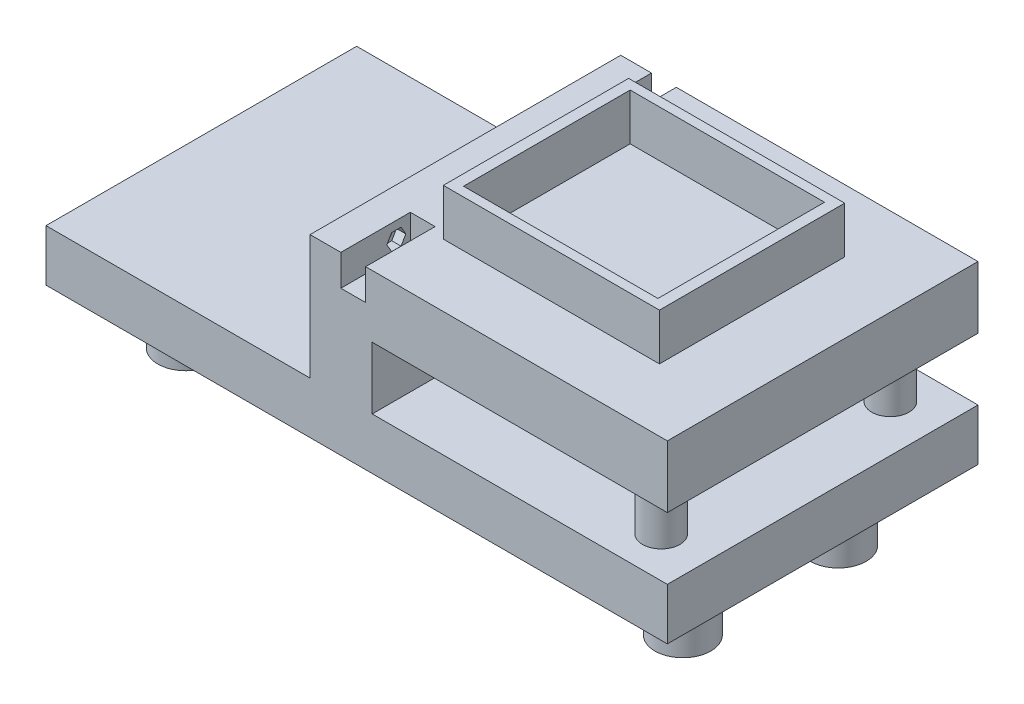
SolidWorks part; units mm, degrees
ref_plane "Front Plane" through (0, 0, 0) normal (0, 0, 1) x (1, 0, 0)
ref_plane "Top Plane" through (0, 0, 0) normal (0, 1, 0) x (1, 0, 0)
ref_plane "Right Plane" through (0, 0, 0) normal (1, 0, 0) x (0, 0, -1)
sketch "Sketch1" plane through (0, 0, 0) normal (0, 1, 0) x (1, 0, 0)
  line L7 (57.5, -50) -> (-57.5, -50)
  line L8 (57.5, -50) -> (57.5, 50)
  line L9 (57.5, 50) -> (-57.5, 50)
  line L10 (-57.5, -50) -> (-57.5, 50)
  line L11 (57.5, -50) -> (-57.5, 50) construction
  line L12 (57.5, 50) -> (-57.5, -50) construction
  point P0 (0, 0)
  dimension "D1" = 115
  dimension "D2" = 100
extrude "Boss-Extrude1" add sketch "Sketch1" along normal blind 20
sketch "Sketch8" plane through (0, 0, 0) normal (0, -1, 0) x (1, 0, 0)
  line L0 (57.5, -50) -> (-57.5, 50) construction
  line L1 (57.5, 50) -> (-57.5, -50) construction
  line L2 (57.5, 0) -> (-57.5, 0) construction
  line L3 (57.5, 50) -> (57.5, -50) construction
  line L4 (-57.5, -50) -> (-57.5, 50) construction
  line L5 (0, -50) -> (0, 50) construction
  line L6 (57.5, -50) -> (-57.5, -50) construction
  line L7 (-57.5, 50) -> (57.5, 50) construction
  circle A0 centre (0, 0) radius 7
  circle A1 centre (42.4079, -36.8764) radius 6
  circle A2 centre (42.4079, 36.8764) radius 6
  dimension "D1" = 12
  dimension "D3" = 14
  dimension "D2" = 20
extrude "Boss-Extrude4" add sketch "Sketch8" along normal blind 20
sketch "Sketch9" plane through (0, -20, 0) normal (0, -1, 0) x (1, 0, 0)
  line L0 (-57.5, 50) -> (57.5, 50) construction
  line L1 (57.5, -50) -> (-142.5, -50)
  line L2 (57.5, -50) -> (57.5, 50)
  line L3 (57.5, 50) -> (-142.5, 50)
  line L4 (-142.5, -50) -> (-142.5, 50)
  line L5 (57.5, -50) -> (-142.5, 50) construction
  line L6 (57.5, 50) -> (-142.5, -50) construction
  line L7 (57.5, 50) -> (57.5, -50) construction
  line L8 (57.5, -50) -> (-57.5, -50) construction
  point P4 (-42.5, 0)
  dimension "D1" = 200
extrude "Boss-Extrude5" add sketch "Sketch9" along normal blind 16.6
sketch "Sketch10" plane through (0, -36.6, 0) normal (0, -1, 0) x (1, 0, 0)
  line L0 (-42.5, -50) -> (-42.5, 50) construction
  line L1 (-142.5, -50) -> (57.5, -50) construction
  line L2 (57.5, 50) -> (-142.5, 50) construction
  line L3 (57.5, 0) -> (-142.5, 0) construction
  line L4 (57.5, -50) -> (57.5, 50) construction
  line L5 (-142.5, 50) -> (-142.5, -50) construction
  circle A0 centre (37.5, -25) radius 9
  circle A1 centre (-122.5, -25) radius 9
  circle A2 centre (-122.5, 25) radius 9
  circle A3 centre (37.5, 25) radius 9
  circle A4 centre (-42.5, 0) radius 10
  dimension "D1" = 18
  dimension "D4" = 20
  dimension "D2" = 20
  dimension "D3" = 25
  dimension "D5" = 20
extrude "Boss-Extrude7" add sketch "Sketch10" along normal blind 20
sketch "Sketch11" plane through (0, 20, 0) normal (0, 1, 0) x (1, 0, 0)
  line L1 (38.07, -32.64) -> (-38.07, -32.64) construction
  line L2 (38.07, -32.64) -> (38.07, 32.64) construction
  line L3 (38.07, 32.64) -> (-38.07, 32.64) construction
  line L4 (-38.07, -32.64) -> (-38.07, 32.64) construction
  line L5 (38.07, -32.64) -> (-38.07, 32.64) construction
  line L6 (38.07, 32.64) -> (-38.07, -32.64) construction
  line L7 (34.93, -29.9479) -> (-34.93, -29.9479) construction
  line L8 (34.93, -29.9479) -> (34.93, 29.9479) construction
  line L9 (34.93, 29.9479) -> (-34.93, 29.9479) construction
  line L10 (-34.93, -29.9479) -> (-34.93, 29.9479) construction
  line L11 (34.93, -29.9479) -> (-34.93, 29.9479) construction
  line L12 (34.93, 29.9479) -> (-34.93, -29.9479) construction
  line L13 (34.78, -29.8193) -> (-34.78, -29.8193)
  line L14 (34.78, -29.8193) -> (34.78, 29.8193)
  line L15 (34.78, 29.8193) -> (-34.78, 29.8193)
  line L16 (-34.78, -29.8193) -> (-34.78, 29.8193)
  line L17 (34.78, -29.8193) -> (-34.78, 29.8193) construction
  line L18 (34.78, 29.8193) -> (-34.78, -29.8193) construction
  line L19 (31.2809, -26.8193) -> (-31.2809, -26.8193)
  line L20 (31.2809, -26.8193) -> (31.2809, 26.8193)
  line L21 (31.2809, 26.8193) -> (-31.2809, 26.8193)
  line L22 (-31.2809, -26.8193) -> (-31.2809, 26.8193)
  line L23 (31.2809, -26.8193) -> (-31.2809, 26.8193) construction
  line L24 (31.2809, 26.8193) -> (-31.2809, -26.8193) construction
  point P0 (0, 0)
  point P6 (0, 0)
  point P11 (0, 0)
  point P16 (0, 0)
  dimension "D1" = 76.14
  dimension "D2" = 65.28
  dimension "D3" = 3.14
  dimension "D4" = 0.15
  dimension "D5" = 3
extrude "Boss-Extrude9" add sketch "Sketch11" along normal blind 15
sketch "Sketch17" plane through (0, 0, 0) normal (0, -1, 0) x (1, 0, 0)
  line L0 (57.5, -50) -> (-57.5, -50) construction
  line L1 (-57.5, 50) -> (-37.5, 50)
  line L2 (-57.5, 50) -> (-57.5, -50)
  line L3 (-57.5, -50) -> (-37.5, -50)
  line L4 (-37.5, 50) -> (-37.5, -50)
  line L5 (-57.5, 50) -> (-37.5, -50) construction
  line L6 (-57.5, -50) -> (-37.5, 50) construction
  point P4 (-47.5, 0)
  dimension "D1" = 20
extrude "Boss-Extrude15" add sketch "Sketch17" along normal blind 20
sketch "Sketch15" plane through (0, -20, 0) normal (0, 1, 0) x (1, 0, 0)
  line L0 (-64.5, 0) -> (-57.5, 0) construction
  line L1 (-142.5, 50) -> (-57.5, 50) construction
  circle A0 centre (-78.6, 0) radius 14.1
  point P4 (0, 0)
  dimension "D1" = 28.2
  dimension "D2" = 50
  dimension "D3" = 7
extrude "Cut-Extrude2" cut sketch "Sketch15" against normal blind 10
sketch "Sketch21" plane through (0, -30, 0) normal (0, 1, 0) x (1, 0, 0)
  circle A0 centre (-85.1607, 0) radius 1.7674
  circle A1 centre (-73.2221, 0) radius 2.0384
extrude "Cut-Extrude3" cut sketch "Sketch21" against normal blind 20 contours A0 | A1
sketch "Sketch19" plane through (-57.5, 0, 0) normal (-1, 0, 0) x (0, 0, 1)
  line L0 (0, 20) -> (0, -20) construction
  line L1 (-50, 20) -> (50, 20) construction
  line L2 (50, -20) -> (-50, -20) construction
  line L3 (0, -13.4091) -> (-33.74, -13.4091) construction
  circle A0 centre (-32.14, -13.4091) radius 1.6
  circle A1 centre (32.14, -13.4091) radius 1.6
  circle A2 centre (-32.14, 14.6909) radius 1.6
  circle A3 centre (32.14, 14.6909) radius 1.6
  point P16 (0, 0)
  dimension "D2" = 3.2
  dimension "D4" = 3.2
  dimension "D1" = 33.74
  dimension "D3" = 28.1
extrude "Cut-Extrude4" cut sketch "Sketch19" against normal blind 38
sketch "Sketch22" plane through (-37.5, 0, 0) normal (1, 0, 0) x (0, 0, -1)
  line L0 (0, 0) -> (0, -20) construction
  line L1 (-29.09, -13.4091) -> (-30.615, -10.7678)
  line L2 (-30.615, -10.7678) -> (-33.665, -10.7678)
  line L3 (-33.665, -10.7678) -> (-35.19, -13.4091)
  line L4 (-35.19, -13.4091) -> (-33.665, -16.0505)
  line L5 (-33.665, -16.0505) -> (-30.615, -16.0505)
  line L6 (-30.615, -16.0505) -> (-29.09, -13.4091)
  line L7 (50, 0) -> (-50, 0) construction
  line L8 (50, -20) -> (-50, -20) construction
  line L9 (30.615, -16.0505) -> (29.09, -13.4091)
  line L10 (33.665, -16.0505) -> (30.615, -16.0505)
  line L11 (35.19, -13.4091) -> (33.665, -16.0505)
  line L12 (33.665, -10.7678) -> (35.19, -13.4091)
  line L13 (30.615, -10.7678) -> (33.665, -10.7678)
  line L14 (29.09, -13.4091) -> (30.615, -10.7678)
  circle A0 centre (-32.14, -13.4091) radius 2.6414 construction
  dimension "D1" = 6.1
extrude "Cut-Extrude5" cut sketch "Sketch22" against normal blind 3
sketch "Sketch23" plane through (0, 20, 0) normal (0, 1, 0) x (1, 0, 0)
  line L0 (-57.5, -50) -> (0, -50) construction
  line L1 (-57.5, -50) -> (57.5, -50) construction
  line L2 (-57.5, -27.6381) -> (-34.78, -27.6381) construction
  line L3 (-57.5, 50) -> (-57.5, -50) construction
  line L4 (-34.78, 29.8193) -> (-34.78, -29.8193) construction
  line L5 (-57.5, 0) -> (-34.78, 0) construction
  line L6 (-47.5916, -27.6381) -> (-39.6141, -27.6381)
  line L7 (-47.5916, -27.6381) -> (-47.5916, -50)
  line L8 (-47.5916, -50) -> (-39.6141, -50)
  line L9 (-39.6141, -27.6381) -> (-39.6141, -50)
  line L10 (-47.5916, -27.6381) -> (-39.6141, -50) construction
  line L11 (-47.5916, -50) -> (-39.6141, -27.6381) construction
  line L12 (-47.5916, 50) -> (-39.6141, 50)
  line L13 (-39.6141, 27.6381) -> (-39.6141, 50)
  line L14 (-47.5916, 27.6381) -> (-39.6141, 27.6381)
  line L15 (-47.5916, 27.6381) -> (-47.5916, 50)
  point P15 (-43.6028, -38.8191)
extrude "Cut-Extrude6" cut sketch "Sketch23" against normal blind 10
sketch "Sketch24" plane through (-47.5916, 0, 0) normal (1, 0, 0) x (0, 0, -1)
  line L0 (-27.6381, 20) -> (-50, 20) construction
  line L1 (-33.665, 17.3322) -> (-35.19, 14.6909)
  line L2 (-35.19, 14.6909) -> (-33.665, 12.0495)
  line L3 (-33.665, 12.0495) -> (-30.615, 12.0495)
  line L4 (-30.615, 12.0495) -> (-29.09, 14.6909)
  line L5 (-29.09, 14.6909) -> (-30.615, 17.3322)
  line L6 (-30.615, 17.3322) -> (-33.665, 17.3322)
  circle A0 centre (-32.14, 14.6909) radius 2.6414 construction
  circle A1 centre (-32.14, 14.6909) radius 1.6 construction
  dimension "D1" = 6.1
extrude "Cut-Extrude7" cut sketch "Sketch24" against normal blind 3
sketch "Sketch25" plane through (-47.5916, 0, 0) normal (1, 0, 0) x (0, 0, -1)
  line L1 (35.19, 14.6909) -> (33.665, 17.3322)
  line L2 (33.665, 17.3322) -> (30.615, 17.3322)
  line L3 (30.615, 17.3322) -> (29.09, 14.6909)
  line L4 (29.09, 14.6909) -> (30.615, 12.0495)
  line L5 (30.615, 12.0495) -> (33.665, 12.0495)
  line L6 (33.665, 12.0495) -> (35.19, 14.6909)
  circle A0 centre (32.14, 14.6909) radius 2.6414 construction
  circle A1 centre (32.14, 14.6909) radius 1.6 construction
  dimension "D1" = 6.1
extrude "Cut-Extrude8" cut sketch "Sketch25" against normal blind 3
